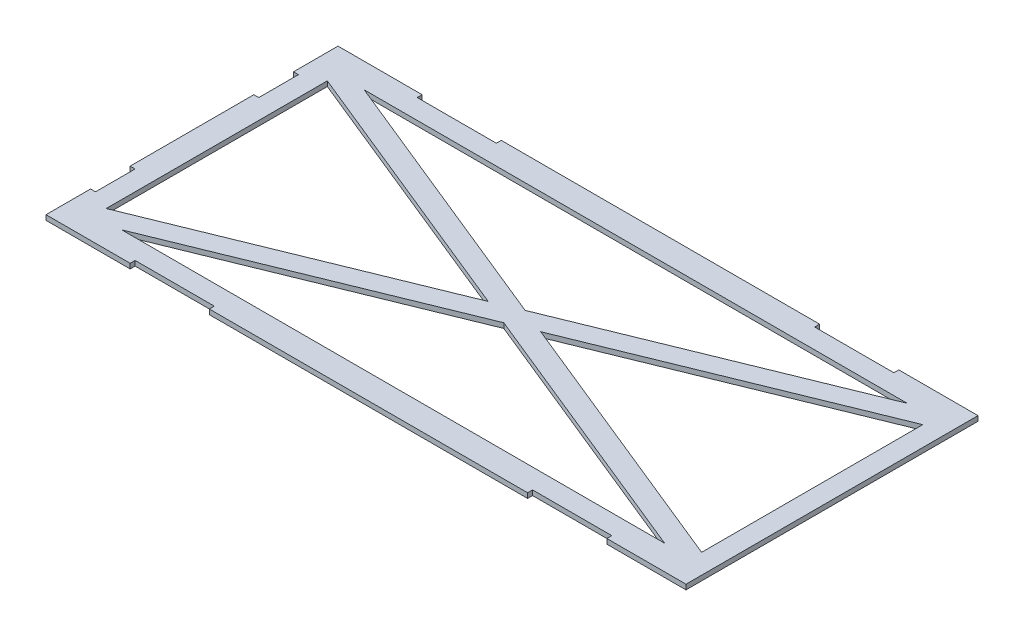
SolidWorks part; units mm, degrees
ref_plane "Front Plane" through (0, 0, 0) normal (0, 0, 1) x (1, 0, 0)
ref_plane "Top Plane" through (0, 0, 0) normal (0, 1, 0) x (1, 0, 0)
ref_plane "Right Plane" through (0, 0, 0) normal (1, 0, 0) x (0, 0, -1)
sketch "Sketch1" plane through (0, 0, 0) normal (0, 1, 0) x (1, 0, 0)
  line L0 (-144.9106, 79.9766) -> (29.2497, 9.0456)
  line L1 (-106.8106, 99.5331) -> (-56.0106, 99.5331)
  line L2 (-157.6106, 74.1331) -> (-157.6106, 48.7331)
  line L3 (-106.8106, -81.4419) -> (-56.0106, -81.4419)
  line L4 (249.78, 99.5331) -> (249.78, -81.4419)
  line L5 (-128.0757, 86.8331) -> (220.245, 86.8331)
  line L6 (-144.9106, 79.9766) -> (-144.9106, -61.8855)
  line L7 (-128.0757, -68.7419) -> (220.245, -68.7419)
  line L8 (237.08, 79.9766) -> (237.08, -61.8855)
  line L9 (-128.0757, 86.8331) -> (46.0847, 15.902)
  line L10 (-144.9106, -61.8855) -> (29.2497, 9.0456)
  line L11 (-128.0757, -68.7419) -> (46.0847, 2.1891)
  line L12 (-144.9106, 86.8331) -> (237.08, -68.7419) construction
  line L13 (237.08, 86.8331) -> (-144.9106, -68.7419) construction
  line L14 (-106.8106, 102.7081) -> (-106.8106, 99.5331)
  line L15 (-106.8106, 99.5331) -> (-56.0106, 99.5331)
  line L16 (-56.0106, 102.7081) -> (-56.0106, 99.5331)
  line L17 (-157.6106, 102.7081) -> (-106.8106, 102.7081)
  line L18 (249.78, 99.5331) -> (249.78, 102.7081)
  line L19 (-56.0106, 102.7081) -> (148.18, 102.7081)
  line L20 (-157.6106, 74.1331) -> (-157.6106, 48.7331)
  line L21 (148.18, 102.7081) -> (148.18, 99.5331)
  line L22 (-160.7856, 99.5331) -> (-160.7856, 74.1331)
  line L23 (-106.8106, -81.4419) -> (-56.0106, -81.4419)
  line L24 (198.98, 102.7081) -> (198.98, 99.5331)
  line L25 (-157.6106, -84.6169) -> (-106.8106, -84.6169)
  line L26 (249.78, -81.4419) -> (249.78, -84.6169)
  line L27 (148.18, -81.4419) -> (198.98, -81.4419)
  line L28 (198.98, -84.6169) -> (249.78, -84.6169)
  line L29 (-157.6106, -84.6169) -> (-160.7856, -84.6169)
  line L30 (-160.7856, -81.4419) -> (-160.7856, -84.6169)
  line L31 (-160.7856, 74.1331) -> (-157.6106, 74.1331)
  line L32 (148.18, 99.5331) -> (198.98, 99.5331)
  line L33 (-157.6106, 102.7081) -> (-160.7856, 102.7081)
  line L34 (-160.7856, 99.5331) -> (-160.7856, 102.7081)
  line L35 (198.98, 102.7081) -> (249.78, 102.7081)
  line L36 (148.18, 99.5331) -> (198.98, 99.5331)
  line L37 (-160.7856, 48.7331) -> (-157.6106, 48.7331)
  line L38 (-160.7856, 48.7331) -> (-160.7856, -30.6419)
  line L39 (-157.6106, -56.0419) -> (-160.7856, -56.0419)
  line L40 (-160.7856, -30.6419) -> (-157.6106, -30.6419)
  line L41 (-160.7856, -56.0419) -> (-160.7856, -81.4419)
  line L42 (-157.6106, -30.6419) -> (-157.6106, -56.0419)
  line L43 (-157.6106, -30.6419) -> (-157.6106, -56.0419)
  line L44 (-106.8106, -81.4419) -> (-106.8106, -84.6169)
  line L45 (-56.0106, -81.4419) -> (-56.0106, -84.6169)
  line L46 (148.18, -81.4419) -> (148.18, -84.6169)
  line L47 (198.98, -81.4419) -> (198.98, -84.6169)
  line L48 (-56.0106, -84.6169) -> (148.18, -84.6169)
  line L49 (46.0847, 15.902) -> (220.245, 86.8331)
  line L50 (46.0847, 2.1891) -> (220.245, -68.7419)
  line L51 (62.9196, 9.0456) -> (237.08, -61.8855)
  line L52 (62.9196, 9.0456) -> (237.08, 79.9766)
  line L53 (148.18, -81.4419) -> (198.98, -81.4419)
  dimension "D1" = 6.35
  dimension "D2" = 6.35
  dimension "D3" = 6.35
  dimension "D4" = 6.35
  dimension "D6" = 12.7
  dimension "D7" = 12.7
  dimension "D8" = 180.975
  dimension "D9" = 12.7
  dimension "D10" = 12.7
  dimension "D11" = 3.175
  dimension "D12" = 3.175
  dimension "D13" = 3.175
  dimension "D14" = 50.8
  dimension "D15" = 50.8
  dimension "D16" = 50.8
  dimension "D17" = 50.8
  dimension "D18" = 25.4
  dimension "D19" = 25.4
  dimension "D20" = 25.4
  dimension "D22" = 50.8
  dimension "D23" = 50.8
  dimension "D25" = 50.8
extrude "Boss-Extrude3" add sketch "Sketch1" along normal blind 3.175 contours L45 L48 L46 L27 L47 L28 L26 L4 L18 L35 L24 L32 L21 L19 L16 L1 L14 L17 L33 L34 L22 L31 L2 L37 L38 L40 L42 L39 L41 L30 L29 L25 L44 L3 L49 L9 L5 L10 L6 L0 L11 L50 L7 L51 L52 L8
